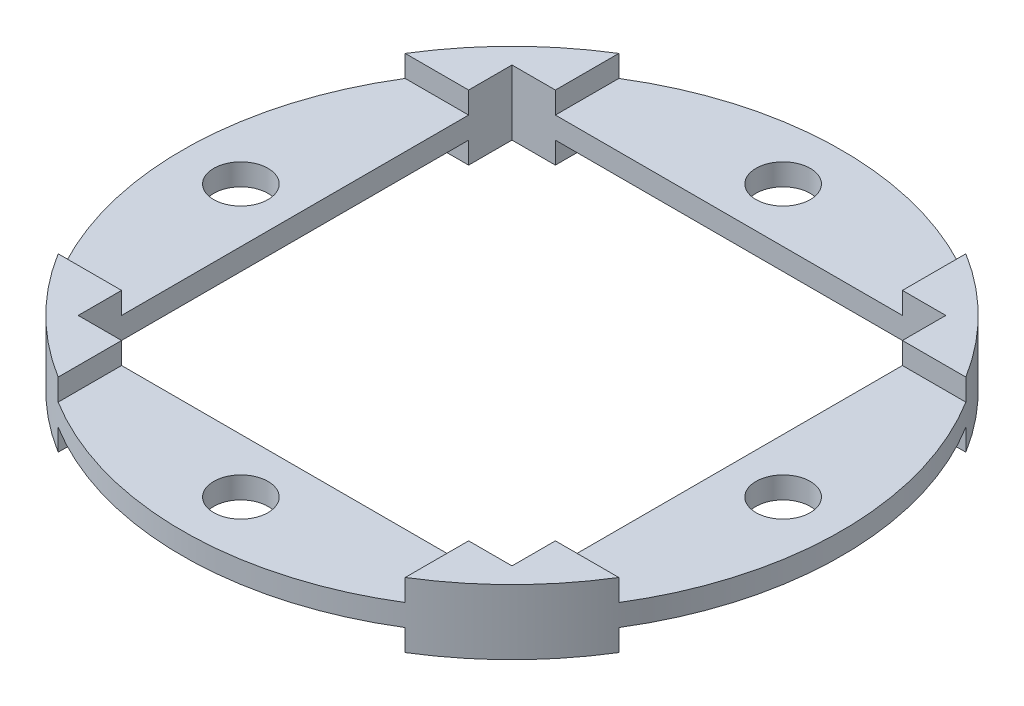
SolidWorks part; units mm, degrees
material "Custom Plastic"
ref_plane "Front Plane" through (0, 0, 0) normal (0, 0, 1) x (1, 0, 0)
ref_plane "Top Plane" through (0, 0, 0) normal (0, 1, 0) x (1, 0, 0)
ref_plane "Right Plane" through (0, 0, 0) normal (1, 0, 0) x (0, 0, -1)
sketch "Sketch1" plane through (0, 0, 0) normal (0, 1, 0) x (1, 0, 0)
  line L0 (0, 0) -> (0, -17.9724) construction
  line L1 (-50, -50) -> (50, -50)
  line L2 (-50, -50) -> (-50, 50)
  line L3 (-50, 50) -> (50, 50)
  line L4 (50, -50) -> (50, 50)
  line L5 (-50, -50) -> (50, 50) construction
  line L6 (-50, 50) -> (50, -50) construction
  line L7 (0, 0) -> (14.9739, 0) construction
  line L8 (0, 62.5) -> (14.3316, 62.5) construction
  line L9 (0, 76) -> (25.822, 76) construction
  circle A0 centre (0, 0) radius 76
  circle A1 centre (0, 0) radius 62.5 construction
  circle A2 centre (0, 62.5) radius 5
  circle A3 centre (62.5, 0) radius 5
  circle A4 centre (0, -62.5) radius 5
  circle A5 centre (-62.5, 0) radius 5
  dimension "D1" = 152
  dimension "D4" = 125
  dimension "D5" = 10
  dimension "D2" = 100
  dimension "D3" = 100
extrude "Boss-Extrude1" add sketch "Sketch1" along normal blind 5 contours A0 | L2 L1 L4 L3
sketch "Sketch2" plane through (0, 5, 0) normal (0, 1, 0) x (1, 0, 0)
  circle A0 centre (0, 0) radius 62.5 construction
  circle A1 centre (-62.5, 0) radius 6.25
  circle A2 centre (0, 62.5) radius 6.25
  circle A3 centre (62.5, 0) radius 6.25
  circle A4 centre (0, -62.5) radius 6.25
  dimension "D1" = 125
  dimension "D3" = 12.5
extrude "Cut-Extrude1" cut sketch "Sketch2" against normal blind 10
sketch "Sketch3" plane through (0, 5, 0) normal (0, 1, 0) x (1, 0, 0)
  line L0 (-50, -50) -> (-40, -50)
  line L3 (-40, -50) -> (-50, -50)
  line L4 (-50, -40) -> (-50, -50)
  line L5 (0, 0) -> (-85.3726, 0) construction
  line L6 (-50, 40) -> (-64.622, 40)
  line L7 (-50, -50) -> (-50, -40)
  line L8 (-50, -40) -> (-64.622, -40)
  line L9 (-40, -50) -> (-40, -64.622)
  line L10 (-50, 40) -> (-50, 50)
  line L11 (-50, 50) -> (-40, 50)
  line L12 (-40, 50) -> (-40, 64.622)
  line L13 (0, 0) -> (0, -29.0709) construction
  line L14 (50, 40) -> (50, 50)
  line L15 (50, 50) -> (40, 50)
  line L16 (40, 50) -> (40, 64.622)
  line L17 (50, 40) -> (64.622, 40)
  line L18 (50, -50) -> (40, -50)
  line L19 (50, -40) -> (50, -50)
  line L20 (50, -40) -> (64.622, -40)
  line L21 (40, -50) -> (40, -64.622)
  arc A0 (-64.622, -40) -> (-40, -64.622) centre (0, 0) ccw
  arc A2 (-64.622, 40) -> (-40, 64.622) centre (0, 0) cw
  arc A3 (64.622, 40) -> (40, 64.622) centre (0, 0) ccw
  arc A4 (64.622, -40) -> (40, -64.622) centre (0, 0) cw
  circle A10 centre (0, 0) radius 76 construction
  line M11 (-50, 50) -> (50, 50)
  line M12 (50, 50) -> (50, -50)
  line M13 (50, -50) -> (-50, -50)
  line M14 (-50, -50) -> (-50, 50)
  circle M15 centre (0, 0) radius 76
  dimension "D3" = 10
  dimension "D1" = 90
  dimension "D2" = 90
  dimension "D4" = 10
extrude "Boss-Extrude2" add sketch "Sketch3" along normal blind 5 contours L21 L20 M13 M15 M12 | L9 L8 M13 M14 M15 | L12 L6 M11 M15 M14 | L17 L16 M12 M15 M11
sketch "Sketch4" plane through (0, 10, 0) normal (0, 1, 0) x (1, 0, 0)
  line L0 (-40, -64.622) -> (-40, -50) construction
  line L1 (-40, -50) -> (-50, -50) construction
  line L2 (-50, -50) -> (-50, -40) construction
  line L3 (-50, -40) -> (-64.622, -40) construction
  line L4 (50, 50) -> (50, 40)
  line L5 (50, 40) -> (64.622, 40)
  line L6 (40, 64.622) -> (40, 50)
  line L7 (40, 50) -> (50, 50)
  line L8 (50, 50) -> (50, 40)
  line L9 (50, 40) -> (64.622, 40)
  line L10 (40, 64.622) -> (40, 50)
  line L11 (40, 50) -> (50, 50)
  line L12 (-50, 50) -> (-40, 50)
  line L13 (-40, 50) -> (-40, 64.622)
  line L14 (-64.622, 40) -> (-50, 40)
  line L15 (-50, 40) -> (-50, 50)
  line L16 (-50, 50) -> (-40, 50)
  line L17 (-40, 50) -> (-40, 64.622)
  line L18 (-64.622, 40) -> (-50, 40)
  line L19 (-50, 40) -> (-50, 50)
  line L20 (50, -50) -> (40, -50) construction
  line L21 (40, -50) -> (40, -64.622) construction
  line L22 (64.622, -40) -> (50, -40) construction
  line L23 (50, -40) -> (50, -50) construction
  line L24 (-40, -64.622) -> (-40, -50)
  line L25 (-40, -50) -> (-50, -50)
  line L26 (-50, -50) -> (-50, -40)
  line L27 (-50, -40) -> (-64.622, -40)
  line L28 (50, -50) -> (40, -50)
  line L29 (40, -50) -> (40, -64.622)
  line L30 (64.622, -40) -> (50, -40)
  line L31 (50, -40) -> (50, -50)
  arc A1 (64.622, 40) -> (40, 64.622) centre (0, 0) ccw
  arc A2 (-64.622, -40) -> (-40, -64.622) centre (0, 0) ccw construction
  arc A3 (40, -64.622) -> (64.622, -40) centre (0, 0) ccw construction
  arc A6 (-40, 64.622) -> (-64.622, 40) centre (0, 0) ccw
  arc A8 (-64.622, -40) -> (-40, -64.622) centre (0, 0) ccw
  arc A9 (40, -64.622) -> (64.622, -40) centre (0, 0) ccw
  arc A13 (64.622, 40) -> (40, 64.622) centre (0, 0) ccw
  arc A14 (-40, 64.622) -> (-64.622, 40) centre (0, 0) ccw
  dimension "D1" = 0
  dimension "D2" = 0
extrude "Boss-Extrude4" add sketch "Sketch4" against normal blind 15
